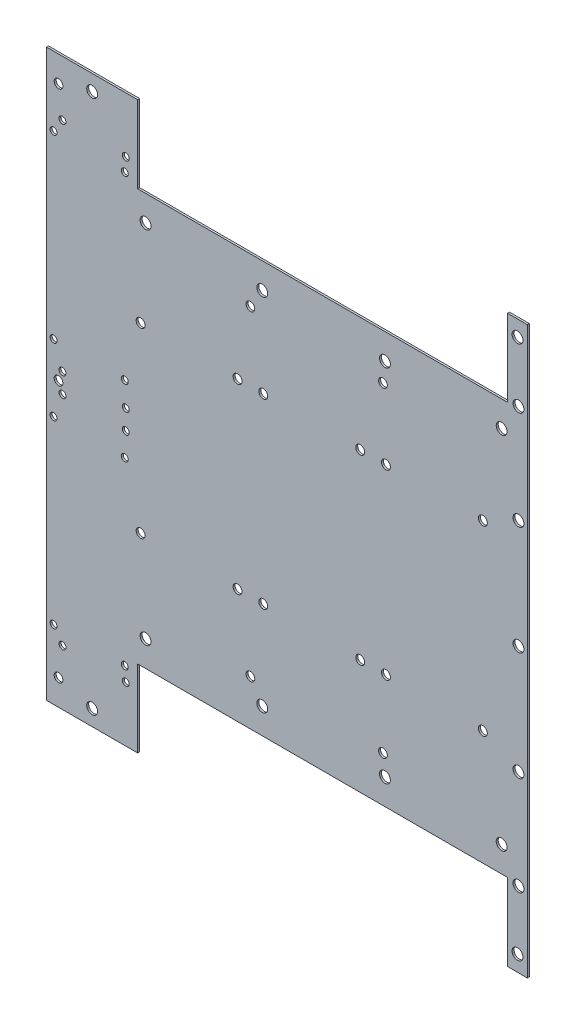
SolidWorks part; units mm, degrees
ref_plane "Front Plane" through (0, 0, 0) normal (0, 0, 1) x (1, 0, 0)
ref_plane "Top Plane" through (0, 0, 0) normal (0, 1, 0) x (1, 0, 0)
ref_plane "Right Plane" through (0, 0, 0) normal (1, 0, 0) x (0, 0, -1)
sketch "Floor, mount and joint holes profile" plane through (0, 0, 0) normal (0, 0, 1) x (1, 0, 0)
  line L0 (-140, -143) -> (-94, -143)
  line L1 (-94, -143) -> (-94, -104)
  line L2 (-94, -104) -> (93, -104)
  line L3 (93, -104) -> (93, -143)
  line L4 (93, -143) -> (103, -143)
  line L5 (103, -143) -> (103, 143)
  line L6 (103, 143) -> (93, 143)
  line L7 (93, 143) -> (93, 104)
  line L8 (93, 104) -> (-94, 104)
  line L9 (-94, 104) -> (-94, 143)
  line L10 (-94, 143) -> (-140, 143)
  line L11 (-140, 143) -> (-140, -143)
  circle A0 centre (-90, -91) radius 2.75
  circle A1 centre (-90, 91) radius 2.75
  circle A2 centre (-31, -91) radius 2.75
  circle A3 centre (-31, 91) radius 2.75
  circle A4 centre (31, -91) radius 2.75
  circle A5 centre (31, 91) radius 2.75
  circle A6 centre (90, -91) radius 2.75
  circle A7 centre (90, 91) radius 2.75
  circle A8 centre (-136.5, -108) radius 1.75
  circle A9 centre (-136.5, -17) radius 1.75
  circle A10 centre (-136.5, 17) radius 1.75
  circle A11 centre (-136.5, 108) radius 1.75
  circle A12 centre (-100.5, -108) radius 1.75
  circle A13 centre (-100.5, -17) radius 1.75
  circle A14 centre (-100.5, 17) radius 1.75
  circle A15 centre (-100.5, 108) radius 1.75
  circle A16 centre (-92.5, -46) radius 2.25
  circle A17 centre (-92.5, 46) radius 2.25
  circle A18 centre (-43.5, -46) radius 2.25
  circle A19 centre (-43.5, 46) radius 2.25
  circle A20 centre (-30.5, -46) radius 2.25
  circle A21 centre (-30.5, 46) radius 2.25
  circle A22 centre (18.5, -46) radius 2.25
  circle A23 centre (18.5, 46) radius 2.25
  circle A24 centre (31.5, -46) radius 2.25
  circle A25 centre (31.5, 46) radius 2.25
  circle A26 centre (80.5, -46) radius 2.25
  circle A27 centre (80.5, 46) radius 2.25
  circle A28 centre (-117, -135) radius 2.75
  circle A29 centre (-117, 135) radius 2.75
  circle A30 centre (98, -135) radius 2.75
  circle A31 centre (98, 135) radius 2.75
  circle A32 centre (98.5, -105) radius 2.75
  circle A33 centre (98.5, -55) radius 2.75
  circle A34 centre (98.5, 0) radius 2.75
  circle A35 centre (98.5, 55) radius 2.75
  circle A36 centre (98.5, 105) radius 2.75
  circle A37 centre (-134, -130) radius 2.2
  circle A38 centre (-134, 0) radius 2.2
  circle A39 centre (-134, 130) radius 2.2
  circle A40 centre (-37, -81) radius 2.2
  circle A41 centre (-37, 81) radius 2.2
  circle A42 centre (30, -81) radius 2.2
  circle A43 centre (30, 81) radius 2.2
  circle A44 centre (-132, -115) radius 1.75
  circle A45 centre (-132, -5) radius 1.75
  circle A46 centre (-132, 5) radius 1.75
  circle A47 centre (-132, 115) radius 1.75
  circle A48 centre (-100, -115) radius 1.75
  circle A49 centre (-100, -5) radius 1.75
  circle A50 centre (-100, 5) radius 1.75
  circle A51 centre (-100, 115) radius 1.75
extrude "Floor, mount and joint holes" add sketch "Floor, mount and joint holes profile" along normal blind 1
